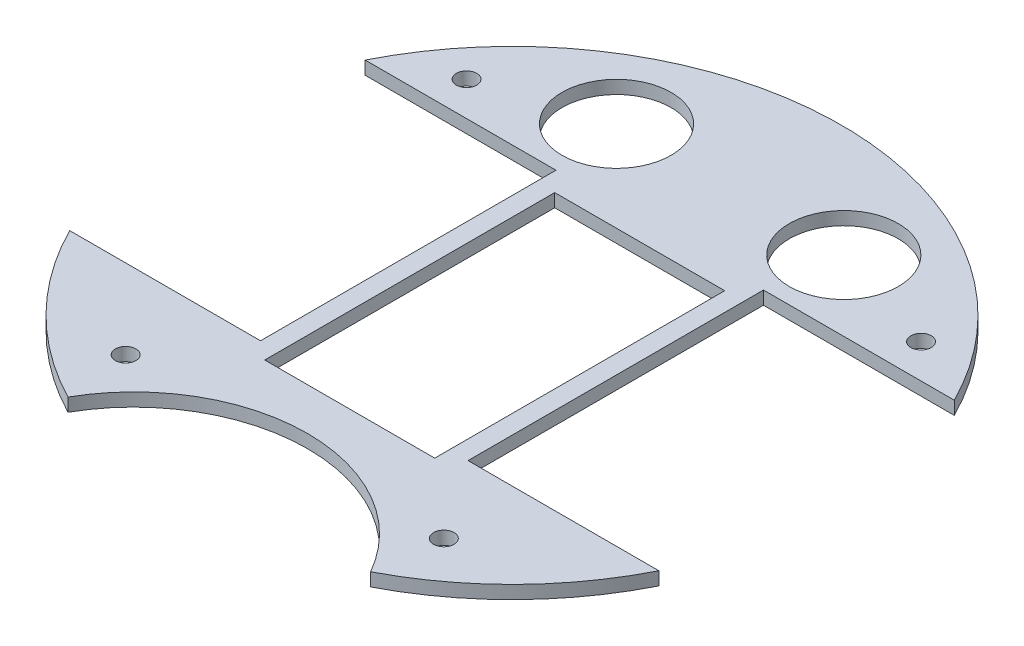
SolidWorks part; units mm, degrees
material "Acrylic (Medium-high impact)"
ref_plane "Front Plane" through (0, 0, 0) normal (0, 0, 1) x (1, 0, 0)
ref_plane "Top Plane" through (0, 0, 0) normal (0, 1, 0) x (1, 0, 0)
ref_plane "Right Plane" through (0, 0, 0) normal (1, 0, 0) x (0, 0, -1)
sketch "Sketch1" plane through (0, 0, 0) normal (0, 1, 0) x (1, 0, 0)
  line L0 (0, -83.2398) -> (-33.2911, -64.4046) construction
  line L1 (0, -83.2398) -> (0, 0) construction
  arc A0 (33.2911, -64.4046) -> (-33.2911, -64.4046) centre (0, 0) ccw
  arc A1 (33.2911, -64.4046) -> (-33.2911, -64.4046) centre (0, -83.2398) ccw
  dimension "D1" = 145
  dimension "D2" = 76.5
  dimension "D3" = 60.5
extrude "Boss-Extrude1" add sketch "Sketch1" along normal blind 2.9
sketch "solenoid placement" plane through (0, 2.9, 0) normal (0, 1, 0) x (1, 0, 0)
  line L4 (-18.7, -35.7) -> (18.7, -35.7)
  line L5 (18.7, -35.7) -> (18.7, 28.1)
  line L6 (18.7, 28.1) -> (-18.7, 28.1)
  line L7 (-18.7, 28.1) -> (-18.7, -35.7)
  line L8 (-18.7, -35.7) -> (18.7, -35.7)
  line L9 (18.7, -35.7) -> (18.7, 28.1)
  line L10 (18.7, 28.1) -> (-18.7, 28.1)
  line L11 (-18.7, 28.1) -> (-18.7, -35.7)
  circle A1 centre (0, 0) radius 72.5 construction
  arc A2 (33.2911, -64.4046) -> (-33.2911, -64.4046) centre (0, 0) ccw construction
  dimension "D1" = 0
extrude "Cut-Extrude1" cut sketch "solenoid placement" against normal through all
sketch "Sketch2" plane through (0, 2.9, 0) normal (0, 1, 0) x (1, 0, 0)
  line L4 (-34.63, -32.5) -> (-22.83, -32.5)
  line L5 (-22.83, -32.5) -> (-22.83, 32.5)
  line L6 (-22.83, 32.5) -> (-64.8074, 32.5)
  line L7 (-64.8074, -32.5) -> (-34.63, -32.5)
  line L8 (-34.63, -32.5) -> (-22.83, -32.5)
  line L9 (-22.83, -32.5) -> (-22.83, 32.5)
  line L10 (-22.83, 32.5) -> (-64.8074, 32.5)
  line L11 (-64.8074, -32.5) -> (-34.63, -32.5)
  line L12 (34.63, -32.5) -> (64.8074, -32.5)
  line L13 (64.8074, 32.5) -> (22.83, 32.5)
  line L14 (22.83, 32.5) -> (22.83, -32.5)
  line L15 (22.83, -32.5) -> (34.63, -32.5)
  line L16 (34.63, -32.5) -> (64.8074, -32.5)
  line L17 (64.8074, 32.5) -> (22.83, 32.5)
  line L18 (22.83, 32.5) -> (22.83, -32.5)
  line L19 (22.83, -32.5) -> (34.63, -32.5)
  arc A2 (-64.8074, 32.5) -> (-64.8074, -32.5) centre (0, 0) ccw
  arc A3 (-64.8074, 32.5) -> (-64.8074, -32.5) centre (0, 0) ccw
  arc A4 (64.8074, -32.5) -> (64.8074, 32.5) centre (0, 0) ccw
  arc A5 (64.8074, -32.5) -> (64.8074, 32.5) centre (0, 0) ccw
  dimension "D2" = 0
  dimension "D1" = 0
extrude "Cut-Extrude2" cut sketch "Sketch2" against normal through all
sketch "Sketch3" plane through (0, 2.9, 0) normal (0, 1, 0) x (1, 0, 0)
  circle A1 centre (25, 48) radius 12
  circle A2 centre (-25, 48) radius 12
  dimension "D1" = 24
extrude "Cut-Extrude3" cut sketch "Sketch3" against normal through all
sketch "Sketch4" plane through (0, 5.8, 0) normal (0, 1, 0) x (1, 0, 0)
  circle A1 centre (35, -50) radius 2.25
  circle A2 centre (35, -50) radius 2.25
  circle A3 centre (-35, -50) radius 2.25
  circle A4 centre (-35, -50) radius 2.25
  circle A5 centre (-50, 40) radius 2.25
  circle A6 centre (-50, 40) radius 2.25
  circle A7 centre (50, 40) radius 2.25
  circle A8 centre (50, 40) radius 2.25
  dimension "D1" = 0
  dimension "D2" = 0
  dimension "D3" = 0
  dimension "D4" = 0
extrude "Cut-Extrude4" cut sketch "Sketch4" against normal through all
equation "\"smallPulleyTeeth\"= 15"
equation "\"largePulleyTeeth\"= 30"
equation "\"eighthThick\"= 2.9mm"
equation "\"sixteenthThick\"= 1.7mm"
equation "\"quarterThick\"=5.9mm"
equation "\"OD\"= 145mm"
equation "\"puckAngle\"= 60.5deg"
equation "\"D1@Sketch1\"=\"OD\""
equation "\"puckDiam\"= 76.5mm"
equation "\"D2@Sketch1\"=\"puckDiam\""
equation "\"D3@Sketch1\"=\"puckAngle\""
equation "\"D1@Boss-Extrude1\"=\"eighthThick\""
equation "\"axlePress\"= 5.9mm"
equation "\"press\"= 0.2mm"
equation "\"wheelClear\"= 0.3mm"
equation "\"10-32clear\"= 4.5mm"
equation "\"6-32clear\"= 3.3mm"
equation "\"8-32clear\"= 4.0mm"
equation "\"wheelHeight\"= 22mm"
equation "\"wheelWell\"= 65mm"
